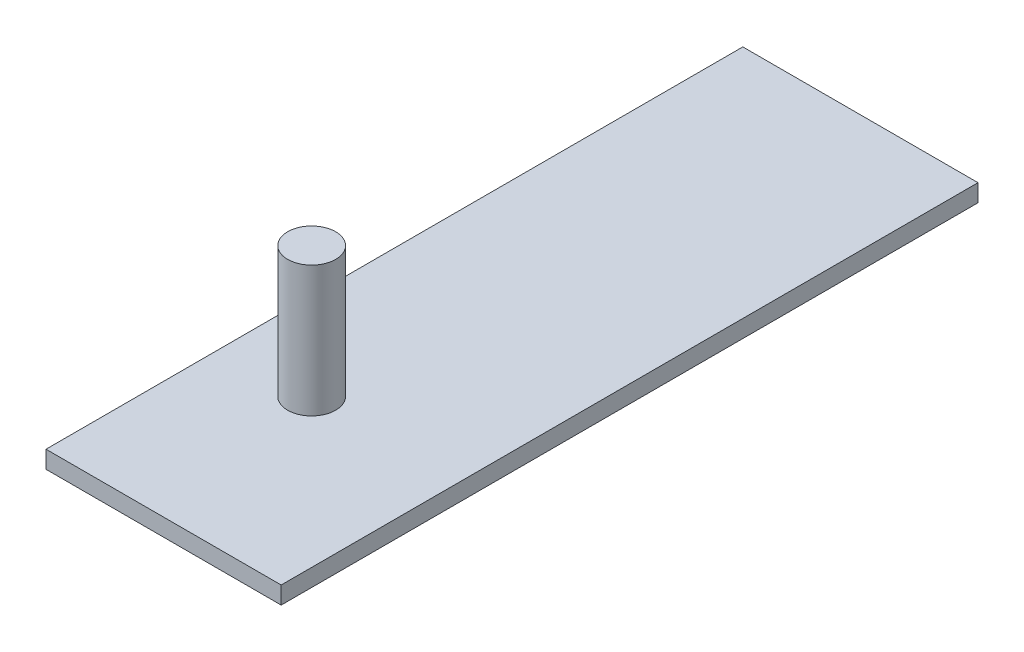
SolidWorks part; units mm, degrees
ref_plane "Front Plane" through (0, 0, 0) normal (0, 0, 1) x (1, 0, 0)
ref_plane "Top Plane" through (0, 0, 0) normal (0, 1, 0) x (1, 0, 0)
ref_plane "Right Plane" through (0, 0, 0) normal (1, 0, 0) x (0, 0, -1)
sketch "Sketch1" plane through (0, 0, 0) normal (0, 1, 0) x (1, 0, 0)
  line L1 (13.5, -40) -> (-13.5, -40)
  line L2 (13.5, -40) -> (13.5, 40)
  line L3 (13.5, 40) -> (-13.5, 40)
  line L4 (-13.5, -40) -> (-13.5, 40)
  line L5 (13.5, -40) -> (-13.5, 40) construction
  line L6 (13.5, 40) -> (-13.5, -40) construction
  point P0 (0, 0)
  dimension "D1" = 80
  dimension "D2" = 27
extrude "Boss-Extrude1" add sketch "Sketch1" along normal blind 2
sketch "Sketch2" plane through (0, 2, 0) normal (0, 1, 0) x (1, 0, 0)
  line L0 (-13.5, 40) -> (-13.5, -40) construction
  line L1 (-13.5, -40) -> (13.5, -40) construction
  circle A0 centre (-3.5, -19.5) radius 2.7536
  dimension "D1" = 10
  dimension "D2" = 20.5
extrude "Boss-Extrude2" add sketch "Sketch2" along normal blind 15
